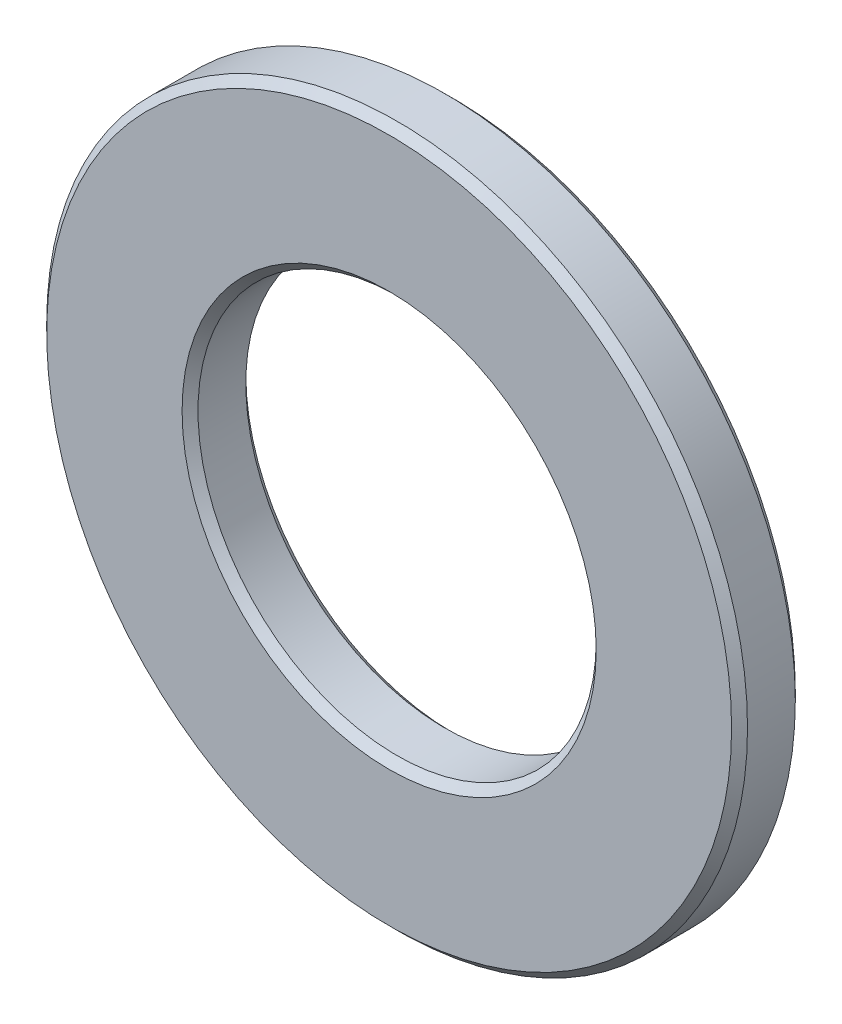
SolidWorks part; units mm, degrees
ref_plane "Płaszczyzna przednia" through (0, 0, 0) normal (0, 0, 1) x (1, 0, 0)
ref_plane "Płaszczyzna górna" through (0, 0, 0) normal (0, 1, 0) x (1, 0, 0)
ref_plane "Płaszczyzna prawa" through (0, 0, 0) normal (1, 0, 0) x (0, 0, -1)
sketch "Szkic1" plane through (0, 0, 0) normal (0, 0, 1) x (1, 0, 0)
  circle A0 centre (0, 0) radius 12.5
  circle A1 centre (0, 0) radius 22
  dimension "D1" = 44
  dimension "D2" = 25
extrude "Dodanie-wyciągnięcie1" add sketch "Szkic1" along normal blind 4
chamfer "Sfazowanie1" distance 0.5 angle 45 4 edges at (12.5, 0, 0) (22, 0, 0) (12.5, 0, 4) (22, 0, 4)
